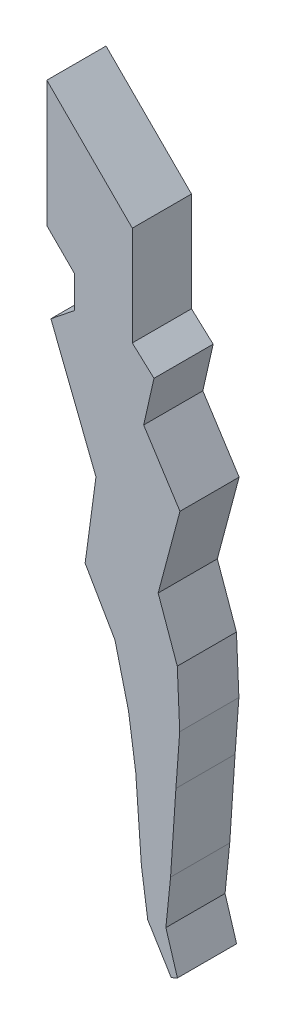
SolidWorks part; units mm, degrees
ref_plane "Ebene vorne" through (0, 0, 0) normal (0, 0, 1) x (1, 0, 0)
ref_plane "Ebene oben" through (0, 0, 0) normal (0, 1, 0) x (1, 0, 0)
ref_plane "Ebene rechts" through (0, 0, 0) normal (1, 0, 0) x (0, 0, -1)
sketch "Model" plane through (0, 0, 0) normal (0, 0, 1) x (1, 0, 0)
  line L25 (0.1, 36.3769) -> (0.1, 29.9889)
  line L26 (0.1, 29.9889) -> (1.4907, 28.5982)
  line L27 (1.4907, 28.5982) -> (1.4907, 26.9556)
  line L28 (1.4907, 26.9556) -> (0.3053, 26.0058)
  line L29 (0.3053, 26.0058) -> (2.5897, 20.2051)
  line L30 (2.5897, 20.2051) -> (2.0401, 16.1408)
  line L31 (2.0401, 16.1408) -> (3.552, 13.5272)
  line L32 (3.552, 13.5272) -> (4.2406, 10.7558)
  line L33 (4.2406, 10.7558) -> (4.6062, 8.2338)
  line L34 (4.6062, 8.2338) -> (4.8939, 4.2827)
  line L35 (4.8939, 4.2827) -> (5.2141, 2.0725)
  line L36 (5.2141, 2.0725) -> (6.4041, 0.1275)
  line L37 (6.4041, 0.1275) -> (6.7193, 0.2704)
  line L38 (6.7193, 0.2704) -> (6.1338, 2.1894)
  line L39 (6.1338, 2.1894) -> (6.3705, 4.5234)
  line L40 (6.3705, 4.5234) -> (6.6416, 8.5537)
  line L41 (6.6416, 8.5537) -> (6.8352, 11.1427)
  line L42 (6.8352, 11.1427) -> (6.711, 13.9556)
  line L43 (6.711, 13.9556) -> (5.7421, 16.6827)
  line L44 (5.7421, 16.6827) -> (6.8478, 20.8235)
  line L45 (6.8478, 20.8235) -> (5.0074, 23.6912)
  line L46 (5.0074, 23.6912) -> (5.5308, 26.0031)
  line L47 (5.5308, 26.0031) -> (4.4315, 27.0062)
  line L48 (4.4315, 27.0062) -> (4.4315, 32.0454)
  line L49 (4.4315, 32.0454) -> (0.1, 36.3769)
extrude "Aufsatz-Linear austragen1" add sketch "Model" along normal blind 3
